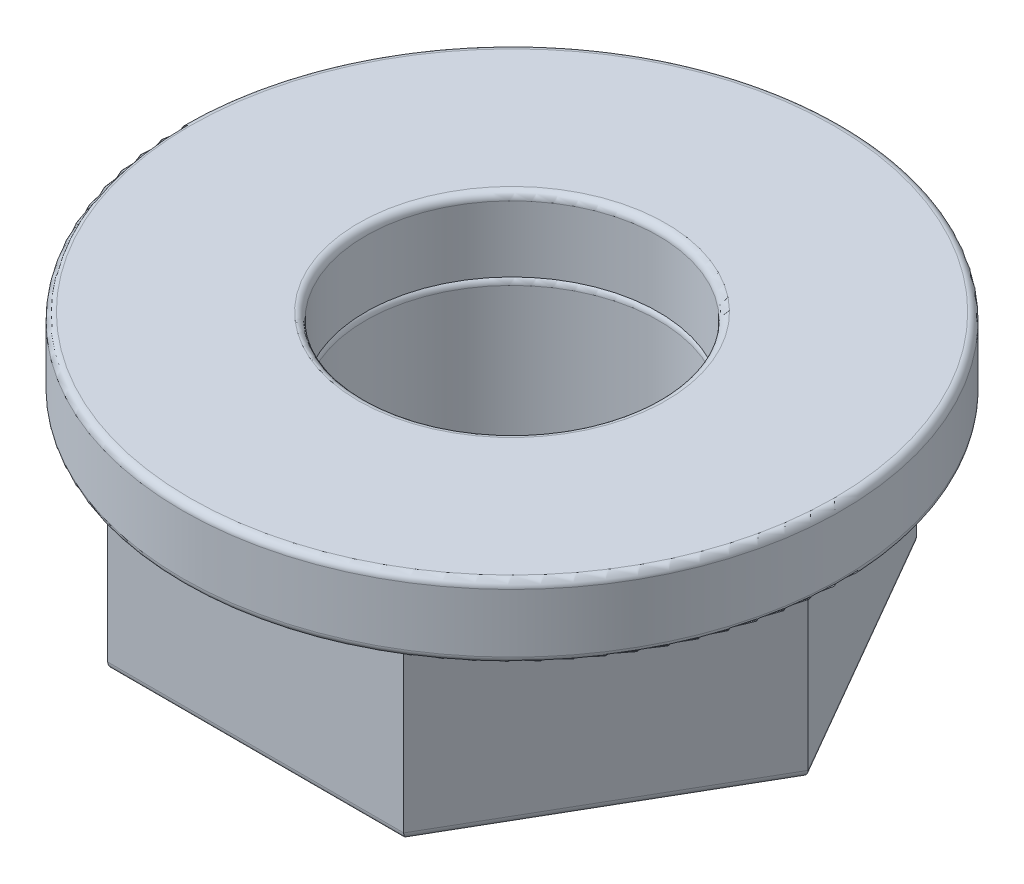
SolidWorks part; units mm, degrees
ref_plane "Front Plane" through (0, 0, 0) normal (0, 0, 1) x (1, 0, 0)
ref_plane "Top Plane" through (0, 0, 0) normal (0, 1, 0) x (1, 0, 0)
ref_plane "Right Plane" through (0, 0, 0) normal (1, 0, 0) x (0, 0, -1)
sketch "Sketch1" plane through (0, 0, 0) normal (0, 1, 0) x (1, 0, 0)
  line L1 (2.0207, -3.5) -> (4.0415, 0)
  line L2 (4.0415, 0) -> (2.0207, 3.5)
  line L3 (2.0207, 3.5) -> (-2.0207, 3.5)
  line L4 (-2.0207, 3.5) -> (-4.0415, 0)
  line L5 (-4.0415, 0) -> (-2.0207, -3.5)
  line L6 (-2.0207, -3.5) -> (2.0207, -3.5)
  circle A0 centre (0, 0) radius 3.5 construction
  circle A1 centre (0, 0) radius 2
  dimension "D1" = 7
  dimension "D2" = 4
extrude "Boss-Extrude1" add sketch "Sketch1" along normal blind 2.5
fillet "Fillet1" radius 0.1 14 edges at (0, 0, 2) (3.0311, 0, 1.75) (3.0311, 0, -1.75) (0, 0, -3.5) (-3.0311, 0, -1.75) (-3.0311, 0, 1.75) (0, 0, 3.5) (0, 2.5, 2) (-3.0311, 2.5, 1.75) (-3.0311, 2.5, -1.75) (0, 2.5, -3.5) (3.0311, 2.5, -1.75) (3.0311, 2.5, 1.75) (0, 2.5, 3.5)
sketch "Sketch2" plane through (0, 2.5, 0) normal (0, 1, 0) x (1, 0, 0)
  circle A0 centre (0, 0) radius 2
  circle A1 centre (0, 0) radius 4.5
  circle A2 centre (0, 0) radius 2 construction
  dimension "D1" = 9
extrude "Boss-Extrude2" add sketch "Sketch2" along normal blind 1
fillet "Fillet2" radius 0.1 3 edges at (0, 3.5, 2) (0, 2.5, 4.5) (0, 3.5, 4.5)
